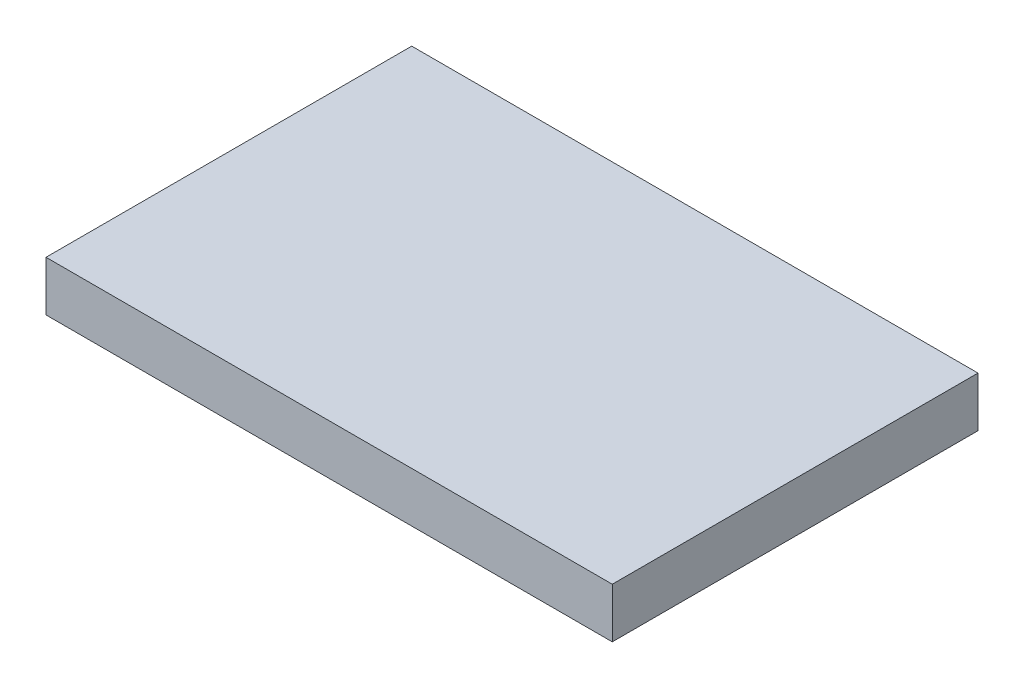
SolidWorks part; units mm, degrees
ref_plane "Front Plane" through (0, 0, 0) normal (0, 0, 1) x (1, 0, 0)
ref_plane "Top Plane" through (0, 0, 0) normal (0, 1, 0) x (1, 0, 0)
ref_plane "Right Plane" through (0, 0, 0) normal (1, 0, 0) x (0, 0, -1)
sketch "Sketch1" plane through (0, 0, 0) normal (0, 1, 0) x (1, 0, 0)
  line L1 (0, 0) -> (72, 0)
  line L2 (0, 0) -> (0, 46.5)
  line L3 (0, 46.5) -> (72, 46.5)
  line L4 (72, 0) -> (72, 46.5)
extrude "Boss-Extrude1" add sketch "Sketch1" along normal blind 6.35
